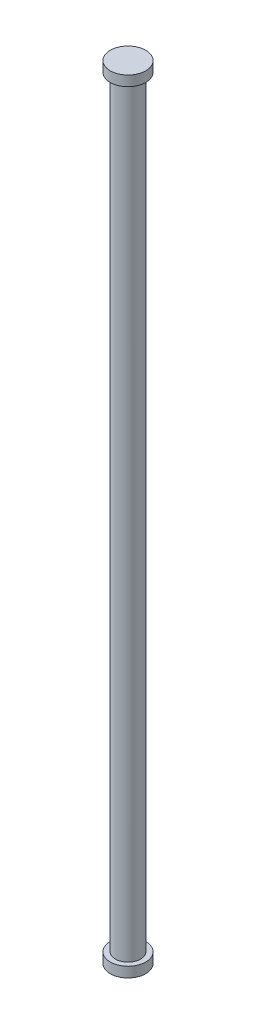
SolidWorks part; units mm, degrees
ref_plane "Front Plane" through (0, 0, 0) normal (0, 0, 1) x (1, 0, 0)
ref_plane "Top Plane" through (0, 0, 0) normal (0, 1, 0) x (1, 0, 0)
ref_plane "Right Plane" through (0, 0, 0) normal (1, 0, 0) x (0, 0, -1)
sketch "Sketch1" plane through (0, 0, 0) normal (0, 1, 0) x (1, 0, 0)
  circle A0 centre (0, 0) radius 2.5
  dimension "D1" = 5
extrude "Boss-Extrude1" add sketch "Sketch1" along normal blind 154
sketch "Sketch2" plane through (0, 0, 0) normal (0, -1, 0) x (1, 0, 0)
  circle A0 centre (0, 0) radius 3.5
  dimension "D1" = 7
extrude "Boss-Extrude2" add sketch "Sketch2" against normal blind 2
sketch "Sketch3" plane through (0, 154, 0) normal (0, 1, 0) x (1, 0, 0)
  circle A0 centre (0, 0) radius 3.5
  dimension "D1" = 7
extrude "Boss-Extrude3" add sketch "Sketch3" against normal blind 2
equation "\"R\"= 150"
